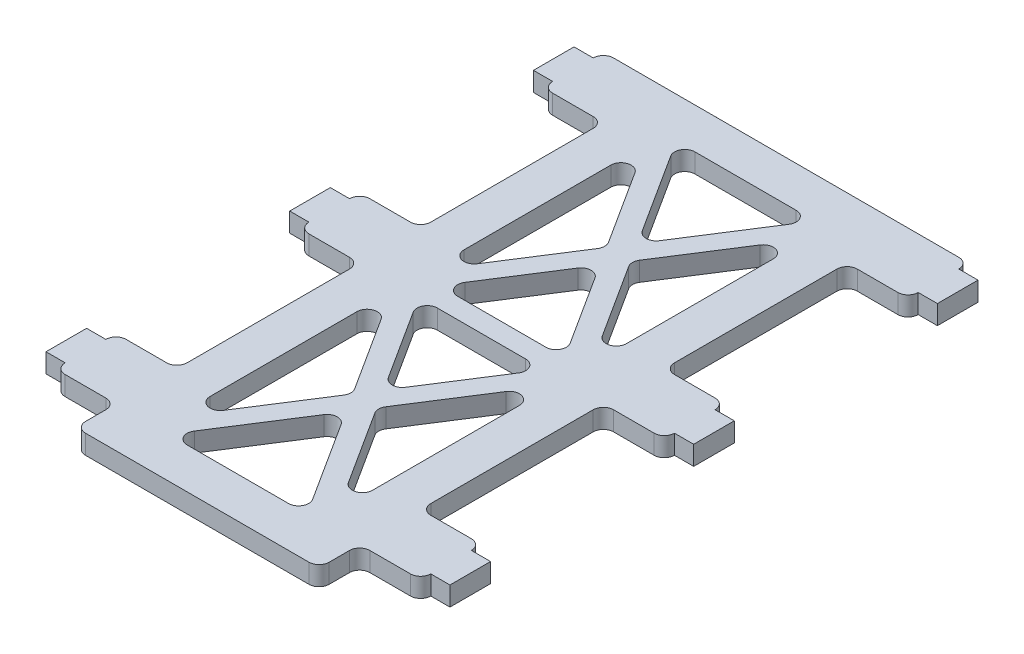
SolidWorks part; units mm, degrees
ref_plane "Front Plane" through (0, 0, 0) normal (0, 0, 1) x (1, 0, 0)
ref_plane "Top Plane" through (0, 0, 0) normal (0, 1, 0) x (1, 0, 0)
ref_plane "Right Plane" through (0, 0, 0) normal (1, 0, 0) x (0, 0, -1)
sketch "Sketch1" plane through (0, 34.29, 0) normal (0, 1, 0) x (1, 0, 0)
  line L0 (22.4028, 180.975) -> (25.4, 180.975) construction
  line L1 (0, -190.5) -> (0, 187.198) construction
  line L2 (38.1028, 187.198) -> (35.1028, 187.198) construction
  line L3 (35.1028, -190.5) -> (38.1, -190.5) construction
  line L5 (-19.05, 74.6125) -> (19.05, 74.6125)
  line L6 (-19.05, 74.6125) -> (-19.05, 166.6875)
  line L7 (-19.05, 166.6875) -> (19.05, 166.6875)
  line L8 (19.05, 74.6125) -> (19.05, 166.6875)
  line L9 (-19.05, 74.6125) -> (19.05, 166.6875) construction
  line L10 (-19.05, 166.6875) -> (19.05, 74.6125) construction
  point P0 (0, 120.65)
  dimension "D1" = 92.075
  dimension "D2" = 38.1
  dimension "D3" = 14.2875
extrude "Boss-Extrude1" add sketch "Sketch1" along normal mid plane 3 contours L7 L8 L5 L6
sketch "Sketch2" plane through (0, 35.79, 0) normal (0, 1, 0) x (1, 0, 0)
  line L0 (0, 166.6875) -> (0, 65.0186) construction
  line L1 (-19.05, 166.6875) -> (19.05, 166.6875) construction
  line L2 (19.05, 123.825) -> (-19.05, 123.825) construction
  line L5 (-28.575, 166.6875) -> (-19.05, 157.1625) construction
  line L6 (28.575, 157.1625) -> (19.05, 157.1625)
  line L7 (28.575, 157.1625) -> (28.575, 166.6875)
  line L8 (28.575, 166.6875) -> (19.05, 166.6875)
  line L9 (19.05, 157.1625) -> (19.05, 166.6875)
  line L10 (28.575, 157.1625) -> (19.05, 166.6875) construction
  line L11 (28.575, 166.6875) -> (19.05, 157.1625) construction
  line L12 (-28.575, 157.1625) -> (-19.05, 166.6875) construction
  line L13 (-19.05, 157.1625) -> (-19.05, 166.6875)
  line L14 (-28.575, 166.6875) -> (-19.05, 166.6875)
  line L15 (-28.575, 157.1625) -> (-28.575, 166.6875)
  line L16 (-28.575, 157.1625) -> (-19.05, 157.1625)
  line L17 (28.575, 119.0625) -> (19.05, 119.0625)
  line L18 (28.575, 119.0625) -> (28.575, 128.5875)
  line L19 (28.575, 128.5875) -> (19.05, 128.5875)
  line L20 (19.05, 119.0625) -> (19.05, 128.5875)
  line L21 (28.575, 119.0625) -> (19.05, 128.5875) construction
  line L22 (28.575, 128.5875) -> (19.05, 119.0625) construction
  line L23 (-19.05, 119.0625) -> (-19.05, 128.5875)
  line L24 (-28.575, 128.5875) -> (-19.05, 128.5875)
  line L25 (-28.575, 119.0625) -> (-28.575, 128.5875)
  line L26 (-28.575, 119.0625) -> (-19.05, 119.0625)
  line L27 (-28.575, 128.5875) -> (-19.05, 119.0625) construction
  line L28 (-28.575, 119.0625) -> (-19.05, 128.5875) construction
  line L29 (28.575, 80.9625) -> (19.05, 80.9625)
  line L30 (28.575, 80.9625) -> (28.575, 90.4875)
  line L31 (28.575, 90.4875) -> (19.05, 90.4875)
  line L32 (19.05, 80.9625) -> (19.05, 90.4875)
  line L33 (28.575, 80.9625) -> (19.05, 90.4875) construction
  line L34 (28.575, 90.4875) -> (19.05, 80.9625) construction
  line L35 (-19.05, 80.9625) -> (-19.05, 90.4875)
  line L36 (-28.575, 90.4875) -> (-19.05, 90.4875)
  line L37 (-28.575, 80.9625) -> (-28.575, 90.4875)
  line L38 (-28.575, 80.9625) -> (-19.05, 80.9625)
  line L39 (-28.575, 90.4875) -> (-19.05, 80.9625) construction
  line L40 (-28.575, 80.9625) -> (-19.05, 90.4875) construction
  point P9 (0, 0)
  point P11 (23.8125, 161.925)
  point P21 (-23.8125, 161.925)
  point P22 (0, 0)
  point P23 (0, 0)
  point P24 (23.8125, 123.825)
  point P33 (-23.8125, 123.825)
  point P34 (23.8125, 85.725)
  point P43 (-23.8125, 85.725)
  dimension "D1" = 9.525
  dimension "D2" = 9.525
  dimension "D4" = 38.1
  dimension "D3" = 3
extrude "Boss-Extrude2" add sketch "Sketch2" against normal up to surface (3 mm away) up to face at (0, 32.79, -120.65)
sketch "Sketch4" plane through (0, 35.79, 0) normal (0, 1, 0) x (1, 0, 0)
  line L0 (19.05, 128.5875) -> (19.05, 157.1625) construction
  line L1 (-12.7, 160.3375) -> (12.7, 160.3375)
  line L2 (-12.7, 160.3375) -> (-12.7, 80.9625)
  line L3 (-12.7, 80.9625) -> (12.7, 80.9625)
  line L4 (12.7, 160.3375) -> (12.7, 80.9625)
  line L5 (-12.7, 160.3375) -> (12.7, 80.9625) construction
  line L6 (-12.7, 80.9625) -> (12.7, 160.3375) construction
  line L7 (-19.05, 128.5875) -> (-19.05, 157.1625) construction
  line L8 (-28.575, 166.6875) -> (28.575, 166.6875) construction
  line L9 (-19.05, 74.6125) -> (19.05, 74.6125) construction
  line L10 (-12.7, 120.65) -> (12.7, 120.65) construction
  line L11 (12.7, 120.65) -> (-12.7, 160.3375) construction
  line L12 (12.7, 120.65) -> (-12.7, 80.9625) construction
  line L13 (-12.7, 120.65) -> (12.7, 160.3375) construction
  line L14 (12.7, 80.9625) -> (-12.7, 120.65) construction
  line L15 (-12.7, 119.0625) -> (12.7, 119.0625)
  line L16 (-12.7, 122.2375) -> (12.7, 122.2375)
  line L17 (14.0371, 81.8182) -> (-10.8152, 120.65)
  line L18 (-10.8152, 120.65) -> (14.0371, 159.4818)
  line L19 (14.5848, 120.65) -> (-11.3629, 80.1068)
  line L20 (14.5848, 120.65) -> (-11.3629, 161.1932)
  line L21 (11.3629, 80.1068) -> (-14.5848, 120.65)
  line L22 (-14.5848, 120.65) -> (11.3629, 161.1932)
  line L23 (10.8152, 120.65) -> (-14.0371, 81.8182)
  line L24 (10.8152, 120.65) -> (-14.0371, 159.4818)
  point P0 (0, 120.65)
  dimension "D1" = 6.35
  dimension "D2" = 6.35
  dimension "D3" = 6.35
  dimension "D4" = 6.35
  dimension "D5" = 1.5875
  dimension "D6" = 1.5875
  dimension "D7" = 1.5875
  dimension "D8" = 1.5875
extrude "Cut-Extrude1" cut sketch "Sketch4" against normal blind 3 contours L15 L19 L17 L4 | L3 L21 L19 | L23 L21 L15 L2 | L23 L15 L17 | L16 L24 L18 | L20 L16 L4 L18 | L20 L22 L1 | L22 L24 L2 L16
fillet "Fillet1" radius 1.5875 48 edges at (-9.7992, 34.29, -119.0625) (9.7992, 34.29, -119.0625) (0, 34.29, -103.7512) (-12.7, 34.29, -117.705) (-1.8848, 34.29, -100.8063) (-12.7, 34.29, -83.9075) (12.7, 34.29, -157.3925) (12.7, 34.29, -123.595) (1.8848, 34.29, -140.4938) (10.8152, 34.29, -160.3375) (0, 34.29, -143.4387) (-10.8152, 34.29, -160.3375) (1.8848, 34.29, -100.8063) (12.7, 34.29, -117.705) (12.7, 34.29, -83.9075) (28.575, 34.29, -80.9625) (28.575, 34.29, -90.4875) (19.05, 34.29, -90.4875) (19.05, 34.29, -119.0625) (28.575, 34.29, -119.0625) (28.575, 34.29, -128.5875) (19.05, 34.29, -128.5875) (19.05, 34.29, -157.1625) (28.575, 34.29, -157.1625) (28.575, 34.29, -166.6875) (-28.575, 34.29, -157.1625) (-19.05, 34.29, -157.1625) (-19.05, 34.29, -128.5875) (-28.575, 34.29, -128.5875) (-28.575, 34.29, -119.0625) (-19.05, 34.29, -119.0625) (-19.05, 34.29, -90.4875) (-28.575, 34.29, -90.4875) (-12.7, 34.29, -123.595) (-12.7, 34.29, -157.3925) (-1.8848, 34.29, -140.4938) (-10.8152, 34.29, -80.9625) (0, 34.29, -97.8613) (10.8152, 34.29, -80.9625) (-9.7992, 34.29, -122.2375) (0, 34.29, -137.5488) (9.7992, 34.29, -122.2375) (-28.575, 34.29, -166.6875) (-19.05, 34.29, -74.6125) (19.05, 34.29, -74.6125) (19.05, 34.29, -80.9625) (-28.575, 34.29, -80.9625) (-19.05, 34.29, -80.9625)
sketch "Sketch5" plane through (0, 35.79, 0) normal (0, 1, 0) x (1, 0, 0)
  line L0 (28.575, 158.75) -> (28.575, 165.1) construction
  line L1 (31.575, 158.75) -> (28.575, 158.75)
  line L2 (31.575, 158.75) -> (31.575, 165.1)
  line L3 (31.575, 165.1) -> (28.575, 165.1)
  line L4 (28.575, 158.75) -> (28.575, 165.1)
  line L5 (31.575, 158.75) -> (28.575, 165.1) construction
  line L6 (31.575, 165.1) -> (28.575, 158.75) construction
  line L7 (28.575, 158.75) -> (28.575, 165.1) construction
  line L8 (28.575, 161.925) -> (30.075, 161.925) construction
  line L9 (0, 196.0278) -> (0, 0) construction
  line L10 (-28.575, 161.925) -> (-30.075, 161.925) construction
  line L11 (-31.575, 165.1) -> (-28.575, 158.75) construction
  line L12 (-31.575, 158.75) -> (-28.575, 165.1) construction
  line L13 (-28.575, 158.75) -> (-28.575, 165.1)
  line L14 (-31.575, 165.1) -> (-28.575, 165.1)
  line L15 (-31.575, 158.75) -> (-31.575, 165.1)
  line L16 (-31.575, 158.75) -> (-28.575, 158.75)
  line L17 (31.575, 120.65) -> (28.575, 120.65)
  line L18 (31.575, 120.65) -> (31.575, 127)
  line L19 (31.575, 127) -> (28.575, 127)
  line L20 (28.575, 120.65) -> (28.575, 127)
  line L21 (31.575, 120.65) -> (28.575, 127) construction
  line L22 (31.575, 127) -> (28.575, 120.65) construction
  line L23 (28.575, 123.825) -> (30.075, 123.825) construction
  line L24 (-28.575, 120.65) -> (-28.575, 127)
  line L25 (-31.575, 127) -> (-28.575, 127)
  line L26 (-31.575, 120.65) -> (-31.575, 127)
  line L27 (-31.575, 120.65) -> (-28.575, 120.65)
  line L28 (-28.575, 123.825) -> (-30.075, 123.825) construction
  line L29 (-31.575, 127) -> (-28.575, 120.65) construction
  line L30 (-31.575, 120.65) -> (-28.575, 127) construction
  line L31 (31.575, 82.55) -> (28.575, 82.55)
  line L32 (31.575, 82.55) -> (31.575, 88.9)
  line L33 (31.575, 88.9) -> (28.575, 88.9)
  line L34 (28.575, 82.55) -> (28.575, 88.9)
  line L35 (31.575, 82.55) -> (28.575, 88.9) construction
  line L36 (31.575, 88.9) -> (28.575, 82.55) construction
  line L37 (28.575, 85.725) -> (30.075, 85.725) construction
  line L38 (-28.575, 82.55) -> (-28.575, 88.9)
  line L39 (-31.575, 88.9) -> (-28.575, 88.9)
  line L40 (-31.575, 82.55) -> (-31.575, 88.9)
  line L41 (-31.575, 82.55) -> (-28.575, 82.55)
  line L42 (-28.575, 85.725) -> (-30.075, 85.725) construction
  line L43 (-31.575, 88.9) -> (-28.575, 82.55) construction
  line L44 (-31.575, 82.55) -> (-28.575, 88.9) construction
  line L45 (-30.075, 161.925) -> (-30.075, 123.825) construction
  point P0 (30.075, 161.925)
  point P7 (30.075, 123.825)
  point P21 (-30.075, 161.925)
  point P35 (-30.075, 123.825)
  point P36 (30.075, 85.725)
  point P49 (-30.075, 85.725)
  dimension "D1" = 3
  dimension "D2" = 6.35
  dimension "D4" = 38.1
  dimension "D3" = 3
extrude "Boss-Extrude3" add sketch "Sketch5" against normal up to surface (3 mm away)
